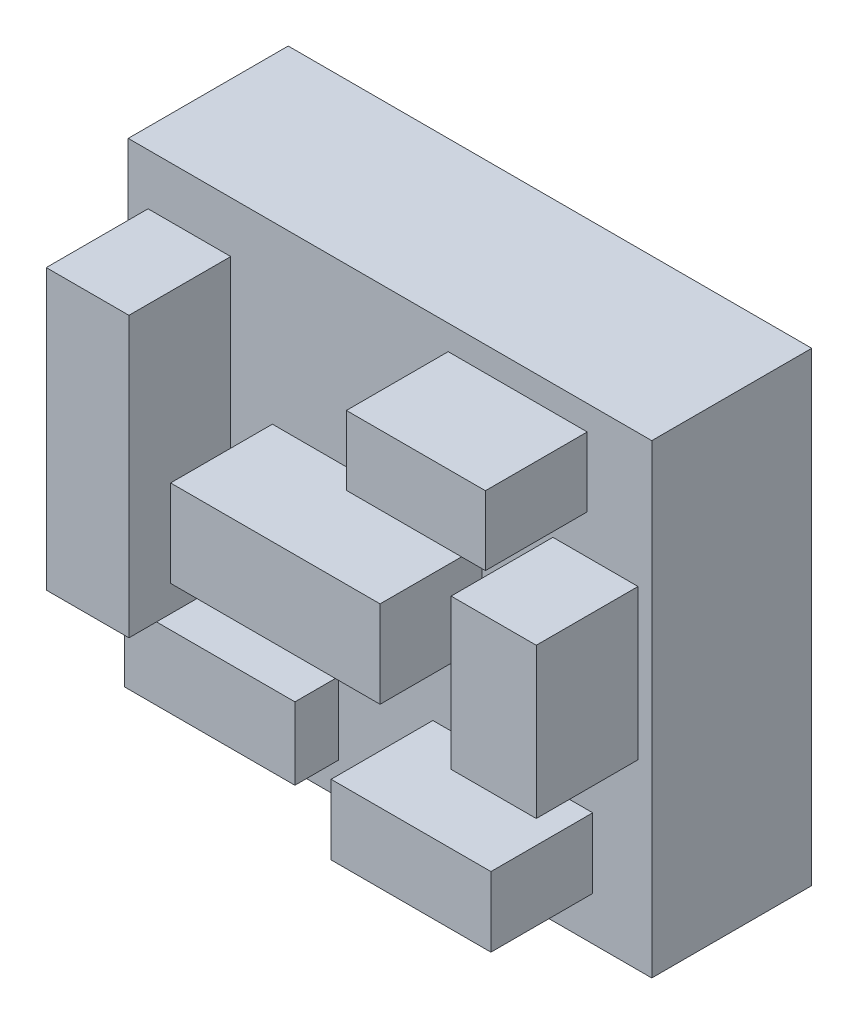
SolidWorks part; units mm, degrees
ref_plane "Front Plane" through (0, 0, 0) normal (0, 0, 1) x (1, 0, 0)
ref_plane "Top Plane" through (0, 0, 0) normal (0, 1, 0) x (1, 0, 0)
ref_plane "Right Plane" through (0, 0, 0) normal (1, 0, 0) x (0, 0, -1)
sketch "Sketch1" plane through (0, 0, 0) normal (0, 0, 1) x (1, 0, 0)
  line L1 (22.86, -20.32) -> (-22.86, -20.32)
  line L2 (22.86, -20.32) -> (22.86, 20.32)
  line L3 (22.86, 20.32) -> (-22.86, 20.32)
  line L4 (-22.86, -20.32) -> (-22.86, 20.32)
  line L5 (22.86, -20.32) -> (-22.86, 20.32) construction
  line L6 (22.86, 20.32) -> (-22.86, -20.32) construction
  point P0 (0, 0)
  dimension "D1" = 40.64
  dimension "D2" = 45.72
extrude "Boss-Extrude1" add sketch "Sketch1" along normal blind 13.97
sketch "Sketch2" plane through (0, 0, 13.97) normal (0, 0, 1) x (1, 0, 0)
  line L1 (-21.1278, 15.8592) -> (-13.9069, 15.8592)
  line L2 (-21.1278, 15.8592) -> (-21.1278, -8.5313)
  line L3 (-21.1278, -8.5313) -> (-13.9069, -8.5313)
  line L4 (-13.9069, 15.8592) -> (-13.9069, -8.5313)
  line L5 (5.0814, 18.1592) -> (17.2232, 18.1592)
  line L6 (5.0814, 18.1592) -> (5.0814, 12.115)
  line L7 (5.0814, 12.115) -> (17.2232, 12.115)
  line L8 (17.2232, 18.1592) -> (17.2232, 12.115)
  line L9 (14.2278, 8.6918) -> (21.6627, 8.6918)
  line L10 (14.2278, 8.6918) -> (14.2278, -4.4128)
  line L11 (14.2278, -4.4128) -> (21.6627, -4.4128)
  line L12 (21.6627, 8.6918) -> (21.6627, -4.4128)
  line L13 (3.7442, -10.4034) -> (17.7046, -10.4034)
  line L14 (3.7442, -10.4034) -> (3.7442, -16.5011)
  line L15 (3.7442, -16.5011) -> (17.7046, -16.5011)
  line L16 (17.7046, -10.4034) -> (17.7046, -16.5011)
  point P16 (5.7232, -16.5011)
  point P17 (3.7442, -10.4034)
  point P18 (14.2278, -4.4128)
  point P19 (17.2232, 12.115)
extrude "Boss-Extrude2" add sketch "Sketch2" along normal blind 8.89
sketch "Sketch3" plane through (0, 0, 13.97) normal (0, 0, 1) x (1, 0, 0)
  line L1 (-10.2697, 5.0011) -> (8.0232, 5.0011)
  line L2 (-10.2697, 5.0011) -> (-10.2697, -2.5942)
  line L3 (-10.2697, -2.5942) -> (8.0232, -2.5942)
  line L4 (8.0232, 5.0011) -> (8.0232, -2.5942)
extrude "Boss-Extrude3" add sketch "Sketch3" along normal blind 8.89
sketch "Sketch4" plane through (0, 0, 13.97) normal (0, 0, 1) x (1, 0, 0)
  line L1 (-19.3627, -11.2058) -> (-4.493, -11.2058)
  line L2 (-19.3627, -11.2058) -> (-19.3627, -17.5173)
  line L3 (-19.3627, -17.5173) -> (-4.493, -17.5173)
  line L4 (-4.493, -11.2058) -> (-4.493, -17.5173)
extrude "Boss-Extrude4" add sketch "Sketch4" along normal blind 3.81
